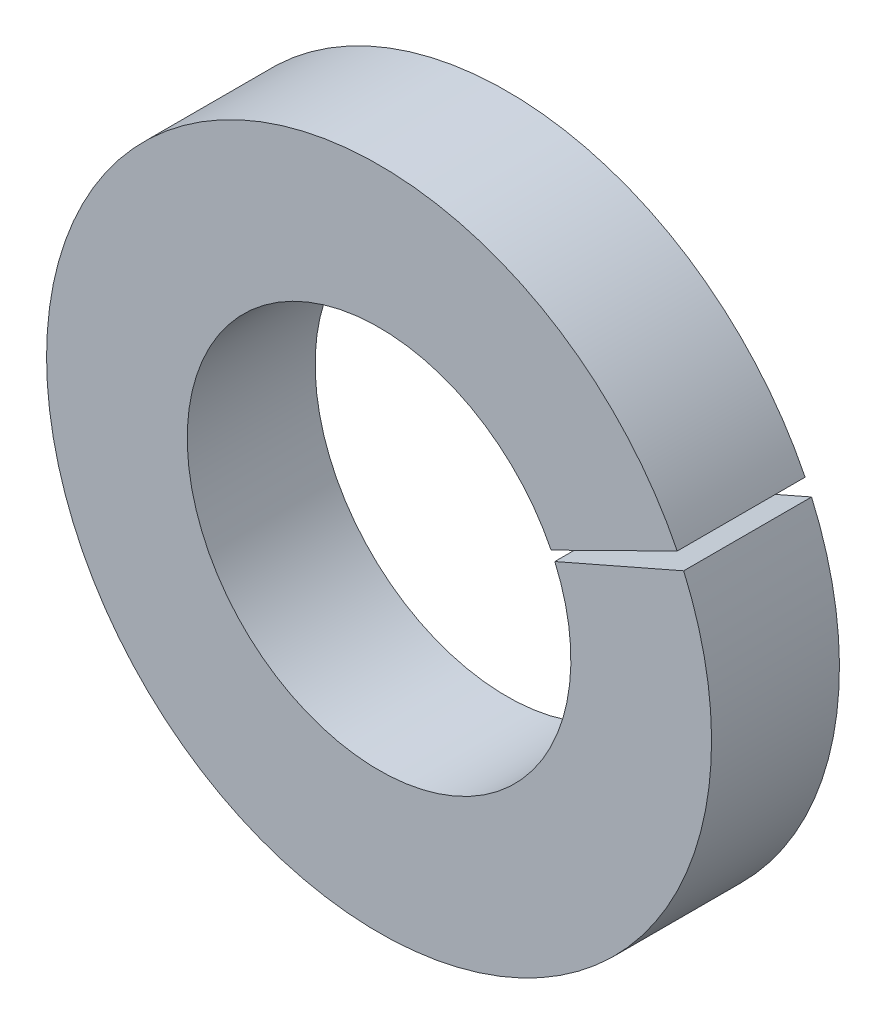
SolidWorks part; units mm, degrees
ref_plane "前视基准面" through (0, 0, 0) normal (0, 0, 1) x (1, 0, 0)
ref_plane "上视基准面" through (0, 0, 0) normal (0, 1, 0) x (1, 0, 0)
ref_plane "右视基准面" through (0, 0, 0) normal (1, 0, 0) x (0, 0, -1)
sketch "草图1" plane through (0, 0, 0) normal (0, 0, 1) x (1, 0, 0)
  circle A0 centre (0, 0) radius 2.6
  circle A1 centre (0, 0) radius 1.5
  dimension "D1" = 3
  dimension "D2" = 5.2
extrude "凸台-拉伸1" add sketch "草图1" along normal blind 1
sketch "草图2" plane through (0, 0, 1) normal (0, 0, 1) x (1, 0, 0)
  line L0 (0, 0) -> (4.8125, 2.3756)
  line L1 (4.8125, 2.3756) -> (4.8125, 2.1059)
  line L2 (4.8125, 2.1059) -> (0, 0)
extrude "切除-拉伸1" cut sketch "草图2" against normal blind 10
